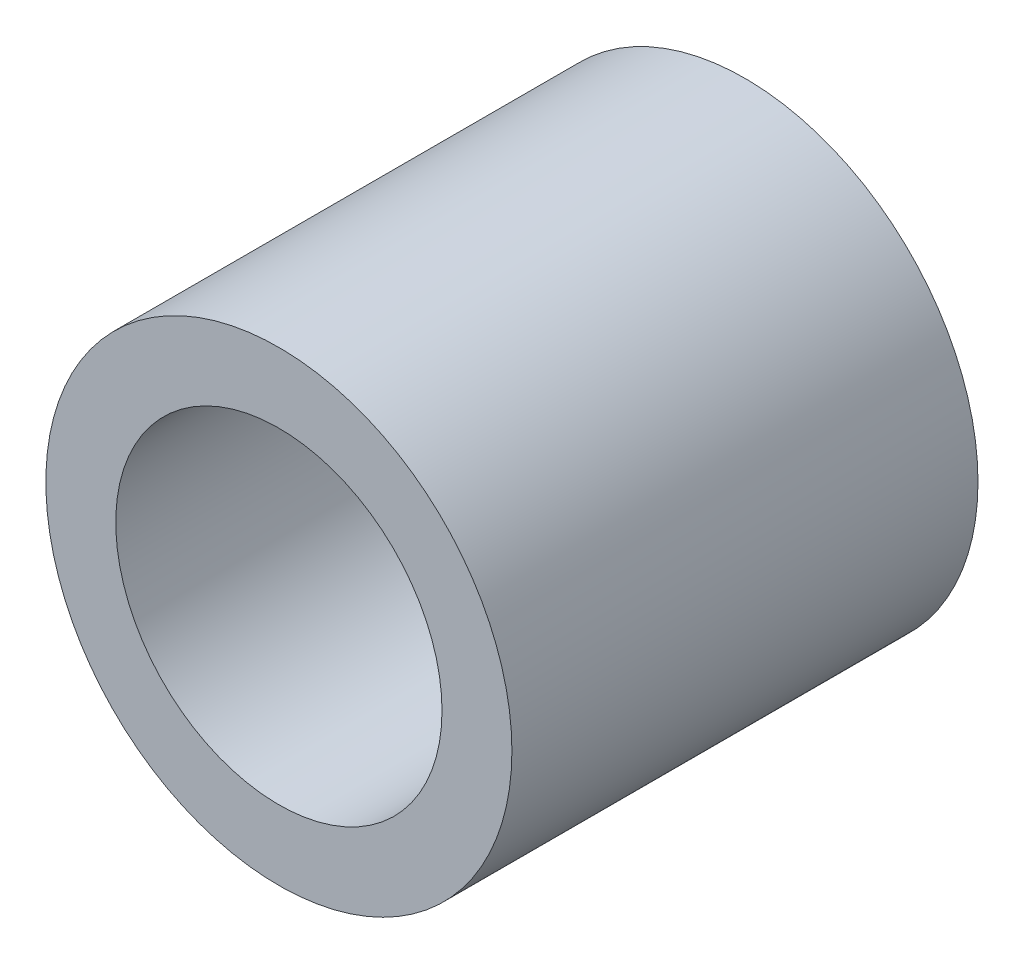
SolidWorks part; units mm, degrees
material "СТ3КП"
ref_plane "Спереди" through (0, 0, 0) normal (0, 0, 1) x (1, 0, 0)
ref_plane "Сверху" through (0, 0, 0) normal (0, 1, 0) x (1, 0, 0)
ref_plane "Справа" through (0, 0, 0) normal (1, 0, 0) x (0, 0, -1)
sketch "Эскиз1" plane through (0, 0, 0) normal (0, 0, 1) x (1, 0, 0)
  circle A0 centre (0, 0) radius 17.5
  circle A1 centre (0, 0) radius 25
  dimension "D1" = 35
  dimension "D2" = 50
extrude "Бобышка-Вытянуть1" add sketch "Эскиз1" along normal blind 50
